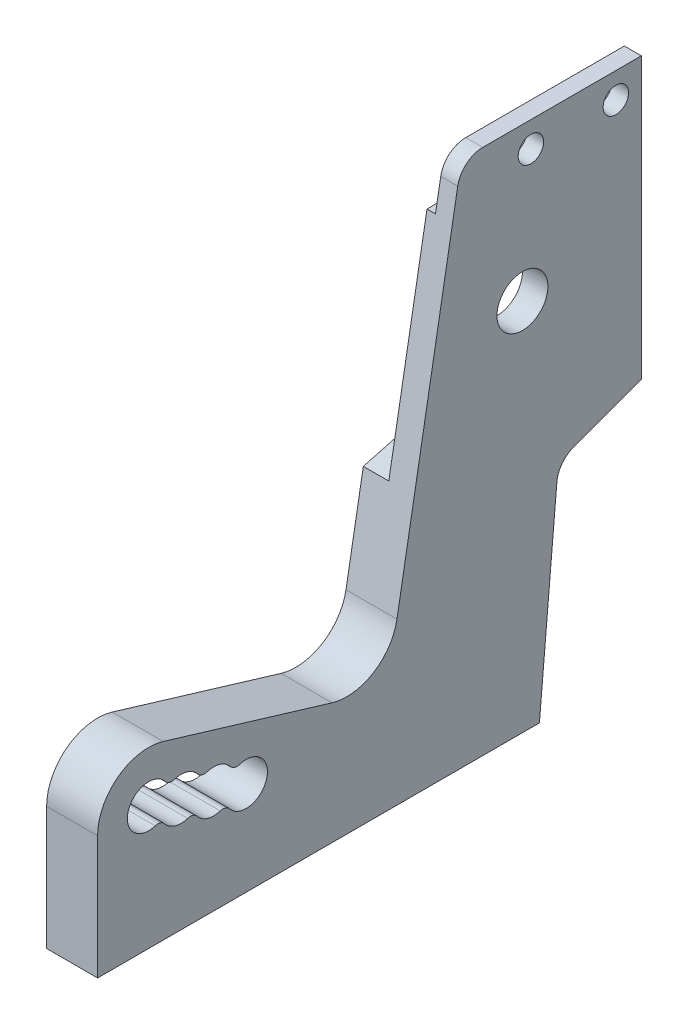
SolidWorks part; units mm, degrees
material "1060 Alloy"
ref_plane "Front Plane" through (0, 0, 0) normal (0, 0, 1) x (1, 0, 0)
ref_plane "Top Plane" through (0, 0, 0) normal (0, 1, 0) x (1, 0, 0)
ref_plane "Right Plane" through (0, 0, 0) normal (1, 0, 0) x (0, 0, -1)
sketch "Sketch1" plane through (0, 0, 0) normal (1, 0, 0) x (0, 0, -1)
  line L1 (0, 0) -> (64, 0)
  line L2 (0, 0) -> (0, 62)
  line L3 (0, 62) -> (64, 62)
  line L4 (64, 0) -> (64, 62)
  circle A0 centre (6, 14.5) radius 2.5
  circle A1 centre (50, 44) radius 3
  dimension "D1" = 6
  dimension "D2" = 5
  dimension "D3" = 14.5
  dimension "D4" = 6
  dimension "D5" = 44
  dimension "D6" = 50
  dimension "D7" = 64
  dimension "D8" = 62
extrude "Boss-Extrude1" add sketch "Sketch1" along normal blind 6
sketch "Sketch2" plane through (6, 0, 0) normal (1, 0, 0) x (0, 0, -1)
  line L0 (0, 62) -> (0, 0) construction
  line L1 (0, 0) -> (64, 0) construction
  line L2 (7.7322, 20.2445) -> (27.5931, 14.2555)
  line L4 (0, 14.5) -> (0, 63)
  line L5 (0, 63) -> (43, 63)
  line L6 (43, 63) -> (35.2342, 18.9581)
  line L7 (64, 62) -> (0, 62) construction
  arc A0 (0, 14.5) -> (7.7322, 20.2445) centre (6, 14.5) cw
  circle A1 centre (50, 44) radius 5 construction
  circle A2 centre (6, 14.5) radius 2.5 construction
  arc A4 (27.5931, 14.2555) -> (35.2342, 18.9581) centre (29.3254, 20) ccw
  dimension "D2" = 10
  dimension "D4" = 80
  dimension "D1" = 1
  dimension "D3" = 43
  dimension "D5" = 20
extrude "Cut-Extrude1" cut sketch "Sketch2" against normal up to next
sketch "Sketch3" plane through (6, 0, 0) normal (1, 0, 0) x (0, 0, -1)
  line L2 (0, 0) -> (64, 0) construction
  line L57 (64, 0) -> (52, 0)
  line L58 (64, 0) -> (64, 29)
  line L59 (64, 29) -> (54.2259, 25.4425)
  line L60 (52, 0) -> (54.2259, 25.4425)
  dimension "D1" = 52
  dimension "D2" = 29
  dimension "D3" = 70
  dimension "D4" = 85
extrude "Cut-Extrude2" cut sketch "Sketch3" against normal up to next
fillet "Fillet1" radius 3 1 edges at (3, 62, -42.8237)
fillet "Fillet2" radius 3 1 edges at (3, 25.4425, -54.2259)
hole_wizard "Tap Drill for M3 Tap1" positions "Sketch5" profile "Sketch4" hole size "M3" standard "ISO"
sketch "Sketch5" plane through (0, 0, 0) normal (0, -1, 0) x (-1, 0, 0)
  line L1 (-6, 0) -> (0, 0) construction
  line L2 (-6, 0) -> (-6, 52) construction
  point P0 (-3, 48)
  point P2 (-3, 12)
  dimension "D1" = 3
  dimension "D2" = 12
  dimension "D3" = 36
sketch "Sketch4" plane through (3, 0, -48) normal (1, 0, 0) x (0, 0, -1)
  line L0 (0, 0) -> (0, 9.7511)
  line L1 (0, 9.7511) -> (1.25, 9)
  line L2 (1.25, 9) -> (1.25, 0)
  line L5 (1.25, 0) -> (0, 0)
  line L10 (0, 9.7511) -> (-1.25, 9) construction
  line L11 (0, -6.35) -> (0, 107.95) construction
  dimension "Hole Dia." = 2.5
  dimension "Hole Depth" = 9
  dimension "Drill Angle" = 118
sketch "Sketch9" plane through (0, 0, 0) normal (-1, 0, 0) x (0, 0, 1)
  line L0 (-64, 62) -> (-64, 35)
  line L1 (-64, 62) -> (-45.341, 62) construction
  line L3 (-64, 29) -> (-64, 62) construction
  line L4 (-64, 62) -> (-42.8237, 62)
  line L5 (-42.8237, 62) -> (-37.2725, 30.5179)
  line L6 (-54, 35) -> (-64, 35)
  line L11 (-35.2342, 18.9581) -> (-42.3865, 59.5209) construction
  line L12 (-37.2725, 30.5179) -> (-54, 35)
  dimension "D1" = 10
  dimension "D2" = 27
  dimension "D5" = 65
extrude "Cut-Extrude3" cut sketch "Sketch9" against normal blind 3
sketch "Sketch10" plane through (3, 0, 0) normal (-1, 0, 0) x (0, 0, 1)
  line L0 (-45.341, 62) -> (-64, 62) construction
  line L1 (-64, 62) -> (-64, 35) construction
  circle A0 centre (-61, 59) radius 1.5
  circle A1 centre (-51, 59) radius 1.5
  dimension "D1" = 3
  dimension "D2" = 3
  dimension "D3" = 3
  dimension "D4" = 10
extrude "Cut-Extrude4" cut sketch "Sketch10" against normal up to next
sketch "Sketch11" plane through (0, 0, 0) normal (-1, 0, 0) x (0, 0, 1)
  line L0 (-6, 14.5) -> (-25.8609, 8.511) construction
  line L1 (-7.7322, 20.2445) -> (-27.5931, 14.2555) construction
  circle A0 centre (-9.8297, 13.3452) radius 2.5
  circle A1 centre (-6, 14.5) radius 2.5 construction
  dimension "D1" = 4
extrude "Cut-Extrude5" cut sketch "Sketch11" against normal up to next
pattern_linear "LPattern1" count 3 spacing 4 along (0, -0.2887, -0.9574) of "Cut-Extrude5"
fillet "Fillet3" radius 1 6 edges at (3, 12.4865, -7.4818) (3, 15.3587, -8.3479) (3, 11.3316, -11.3114) (3, 14.2039, -12.1776) (3, 13.0491, -16.0072) (3, 10.1768, -15.1411)
sketch "Sketch12" plane through (3, 0, 0) normal (-1, 0, 0) x (0, 0, 1)
  line L1 (-64, 62) -> (-41.0174, 62)
  line L2 (-64, 62) -> (-64, 56)
  line L3 (-64, 56) -> (-41.0174, 56)
  line L4 (-41.0174, 62) -> (-41.0174, 56)
  dimension "D1" = 6
extrude "Cut-Extrude6" cut sketch "Sketch12" against normal blind 1
